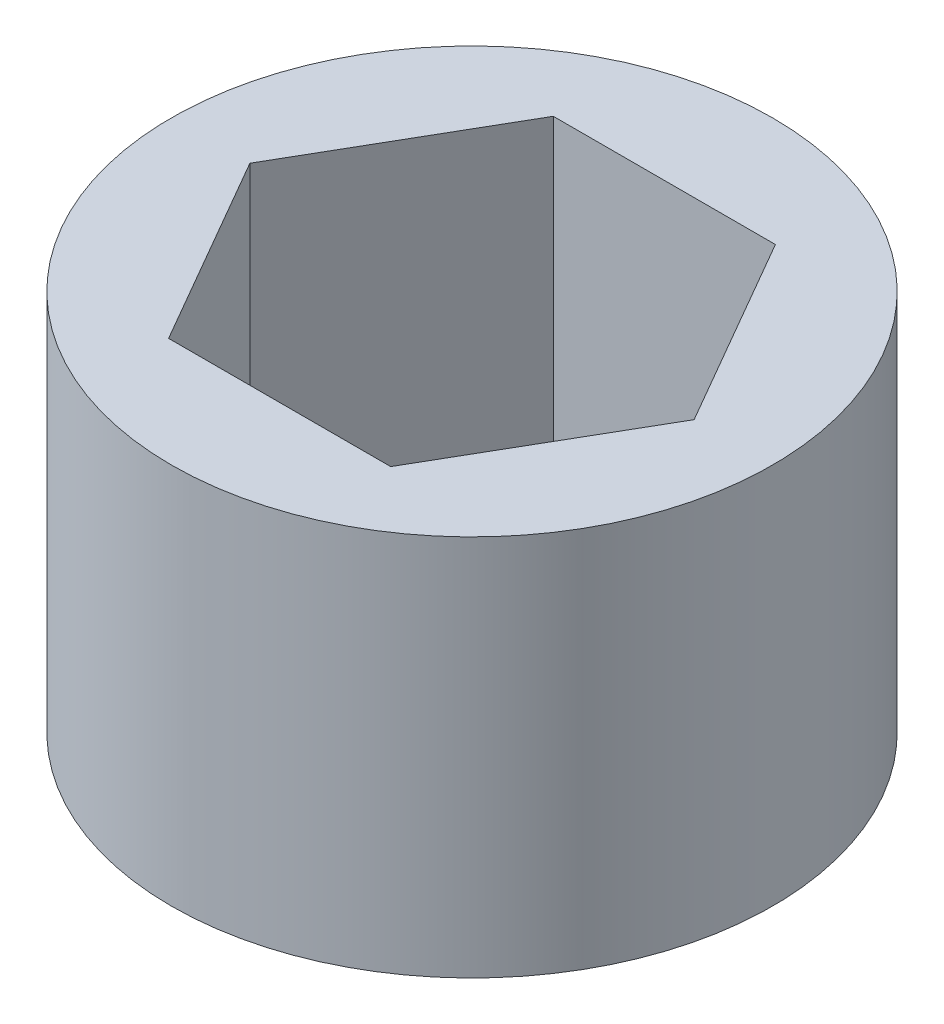
SolidWorks part; units mm, degrees
ref_plane "Front Plane" through (0, 0, 0) normal (0, 0, 1) x (1, 0, 0)
ref_plane "Top Plane" through (0, 0, 0) normal (0, 1, 0) x (1, 0, 0)
ref_plane "Right Plane" through (0, 0, 0) normal (1, 0, 0) x (0, 0, -1)
sketch "Sketch1" plane through (0, 0, 0) normal (0, 1, 0) x (1, 0, 0)
  line L1 (7.3837, 0) -> (3.6918, 6.3944)
  line L2 (3.6918, 6.3944) -> (-3.6918, 6.3944)
  line L3 (-3.6918, 6.3944) -> (-7.3837, 0)
  line L4 (-7.3837, 0) -> (-3.6918, -6.3945)
  line L5 (-3.6918, -6.3945) -> (3.6918, -6.3944)
  line L6 (3.6918, -6.3944) -> (7.3837, 0)
  circle A0 centre (0, 0) radius 6.3944 construction
  circle A1 centre (0, 0) radius 9.9949
  dimension "D1" = 12.7889
  dimension "D2" = 19.9898
extrude "Boss-Extrude1" add sketch "Sketch1" along normal blind 12.7
